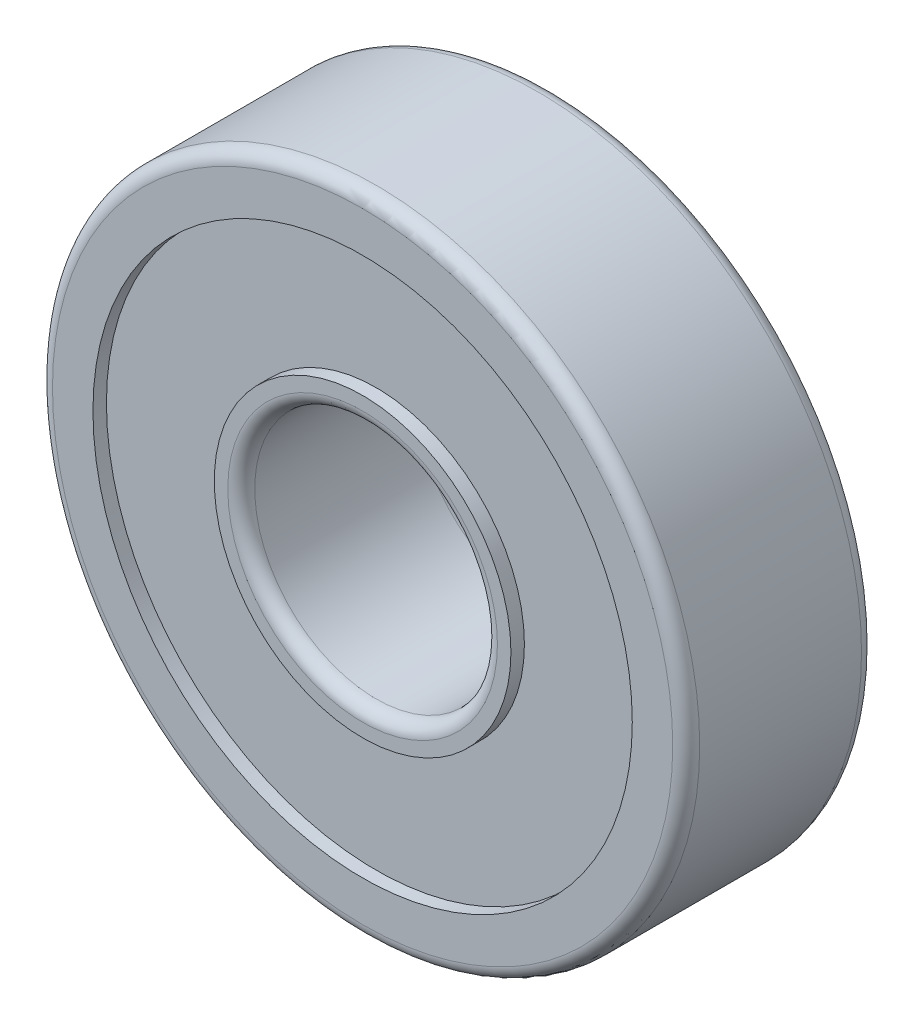
SolidWorks part; units mm, degrees
ref_plane "Front Plane" through (0, 0, 0) normal (0, 0, 1) x (1, 0, 0)
ref_plane "Top Plane" through (0, 0, 0) normal (0, 1, 0) x (1, 0, 0)
ref_plane "Right Plane" through (0, 0, 0) normal (1, 0, 0) x (0, 0, -1)
sketch "Sketch1" plane through (0, 0, 0) normal (0, 0, 1) x (1, 0, 0)
  circle A0 centre (0, 0) radius 12
  circle A1 centre (0, 0) radius 4.5
  dimension "D1" = 24
  dimension "D2" = 9
extrude "Boss-Extrude1" add sketch "Sketch1" along normal mid plane 7
fillet "Fillet1" radius 0.5 4 edges at (4.5, 0, 3.5) (4.5, 0, -3.5) (12, 0, -3.5) (12, 0, 3.5)
sketch "Sketch2" plane through (0, 0, 3.5) normal (0, 0, 1) x (1, 0, 0)
  circle A0 centre (0, 0) radius 5.5
  circle A1 centre (0, 0) radius 4.5 construction
  circle A2 centre (0, 0) radius 10
  circle A3 centre (0, 0) radius 12 construction
  dimension "D1" = 1
  dimension "D2" = 2
extrude "Cut-Extrude1" cut sketch "Sketch2" against normal blind 0.5
mirror "Mirror1" about plane through (0, 0, 0) normal (0, 0, 1) of "Cut-Extrude1"
